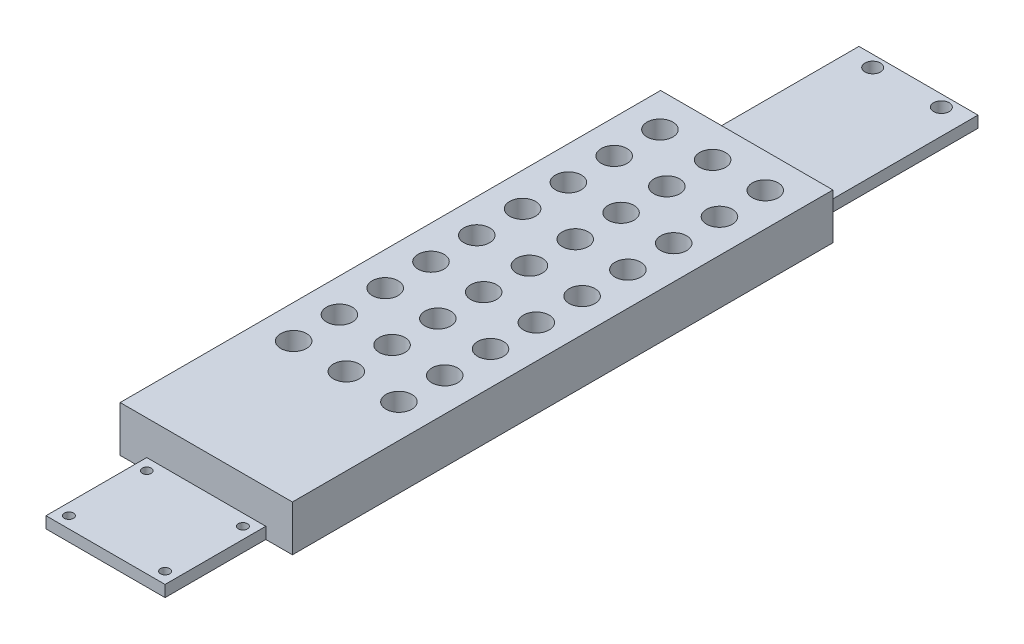
SolidWorks part; units mm, degrees
ref_plane "Front Plane" through (0, 0, 0) normal (0, 0, 1) x (1, 0, 0)
ref_plane "Top Plane" through (0, 0, 0) normal (0, 1, 0) x (1, 0, 0)
ref_plane "Right Plane" through (0, 0, 0) normal (1, 0, 0) x (0, 0, -1)
sketch "Sketch1" plane through (0, 0, 0) normal (0, 1, 0) x (1, 0, 0)
  line L0 (26, -118.035) -> (26, -162.035)
  line L1 (37.625, -118.035) -> (26, -118.035)
  line L2 (37.625, -118.035) -> (37.625, 118.035)
  line L3 (37.625, 118.035) -> (26, 118.035)
  line L4 (-37.625, -118.035) -> (-37.625, 118.035)
  line L5 (37.625, -118.035) -> (-37.625, 118.035) construction
  line L6 (37.625, 118.035) -> (-37.625, -118.035) construction
  line L7 (26, -162.035) -> (-26, -162.035)
  line L8 (-26, -162.035) -> (-26, -118.035)
  line L9 (-26, -118.035) -> (-37.625, -118.035)
  line L10 (0, -162.035) -> (0, -96.035) construction
  line L11 (-21, -123.035) -> (0, -129.035) construction
  line L12 (0, -129.035) -> (21, -123.035) construction
  line L13 (-55, 0) -> (55, 0) construction
  line L14 (0, 129.035) -> (15, 129.035) construction
  line L15 (-15, 129.035) -> (0, 129.035) construction
  line L16 (0, 162.035) -> (0, 96.035) construction
  line L17 (-26, 193.035) -> (-26, 118.035)
  line L18 (26, 193.035) -> (-26, 193.035)
  line L19 (26, 118.035) -> (26, 193.035)
  line L20 (-26, 118.035) -> (-37.625, 118.035)
  line L21 (0, 162.035) -> (0, 95.5) construction
  line L22 (-15, 188.035) -> (0, 188.035) construction
  line L23 (0, 188.035) -> (15, 188.035) construction
  circle A0 centre (-21, -123.035) radius 2
  circle A1 centre (21, -123.035) radius 2
  circle A2 centre (-21, -157.035) radius 2
  circle A3 centre (21, -157.035) radius 2
  circle A4 centre (15, 188.035) radius 3.4
  circle A5 centre (-15, 188.035) radius 3.4
  circle A6 centre (15, 129.035) radius 3.4
  circle A7 centre (-15, 129.035) radius 3.4
  circle A8 centre (-22.995, 103.115) radius 5.65
  circle A9 centre (0.005, 103.115) radius 5.65
  circle A10 centre (23.005, 103.115) radius 5.65
  circle A11 centre (0.005, 83.115) radius 5.65
  circle A12 centre (23.005, 83.115) radius 5.65
  circle A13 centre (0.005, 63.115) radius 5.65
  circle A14 centre (23.005, 63.115) radius 5.65
  circle A15 centre (0.005, 43.115) radius 5.65
  circle A16 centre (23.005, 43.115) radius 5.65
  circle A17 centre (0.005, 23.115) radius 5.65
  circle A18 centre (23.005, 23.115) radius 5.65
  circle A19 centre (0.005, 3.115) radius 5.65
  circle A20 centre (23.005, 3.115) radius 5.65
  circle A21 centre (0.005, -16.885) radius 5.65
  circle A22 centre (23.005, -16.885) radius 5.65
  circle A23 centre (0.005, -36.885) radius 5.65
  circle A24 centre (23.005, -36.885) radius 5.65
  circle A25 centre (0.005, -56.885) radius 5.65
  circle A26 centre (23.005, -56.885) radius 5.65
  circle A27 centre (-22.995, 83.115) radius 5.65
  circle A28 centre (-22.995, 63.115) radius 5.65
  circle A29 centre (-22.995, 43.115) radius 5.65
  circle A30 centre (-22.995, 23.115) radius 5.65
  circle A31 centre (-22.995, 3.115) radius 5.65
  circle A32 centre (-22.995, -16.885) radius 5.65
  circle A33 centre (-22.995, -36.885) radius 5.65
  circle A34 centre (-22.995, -56.885) radius 5.65
  point P0 (0, 0)
  point P22 (0, 0)
  point P24 (0, 0)
  point P95 (0, 0)
  point P97 (-15, 159.6638)
  point P98 (0, 0)
  point P99 (0, 0)
  point P100 (0, 0)
  point P101 (0, 0)
  dimension "D1" = 4
  dimension "D9" = 11.3
  dimension "D16" = 6.8
  dimension "D2" = 42
  dimension "D3" = 5
  dimension "D4" = 75.25
  dimension "D5" = 34
  dimension "D6" = 5
  dimension "D7" = 61.15
  dimension "D8" = 5
  dimension "D10" = 14.92
  dimension "D11" = 14.63
  dimension "D14" = 20
  dimension "D15" = 23
  dimension "D17" = 30
  dimension "D18" = 59
  dimension "D19" = 11
  dimension "D20" = 5
  dimension "D21" = 52
  dimension "D22" = 52
  dimension "D12" = 3
  dimension "D13" = 9
extrude "Boss-Extrude1" add sketch "Sketch1" along normal blind 20 contours L17 L20 L4 L9 L8 L7 L0 L1 L2 L3 L19 L18 A34 A33 A32 A31 A30 A29 A28 A27 A26 A25 A24 A23 A22 A21 A20 A19 A18 A17 A16
sketch "Sketch2" plane through (0, 20, 0) normal (0, 1, 0) x (1, 0, 0)
  line L1 (-26, -118.035) -> (26, -118.035)
  line L2 (-26, -118.035) -> (-26, -162.035)
  line L3 (-26, -162.035) -> (26, -162.035)
  line L4 (26, -118.035) -> (26, -162.035)
  line L5 (-26, 193.035) -> (26, 193.035)
  line L6 (-26, 193.035) -> (-26, 118.035)
  line L7 (-26, 118.035) -> (26, 118.035)
  line L8 (26, 193.035) -> (26, 118.035)
extrude "Cut-Extrude1" cut sketch "Sketch2" against normal offset from surface (15 mm away) 5 up to face at (-22.995, 0, 62.535)
